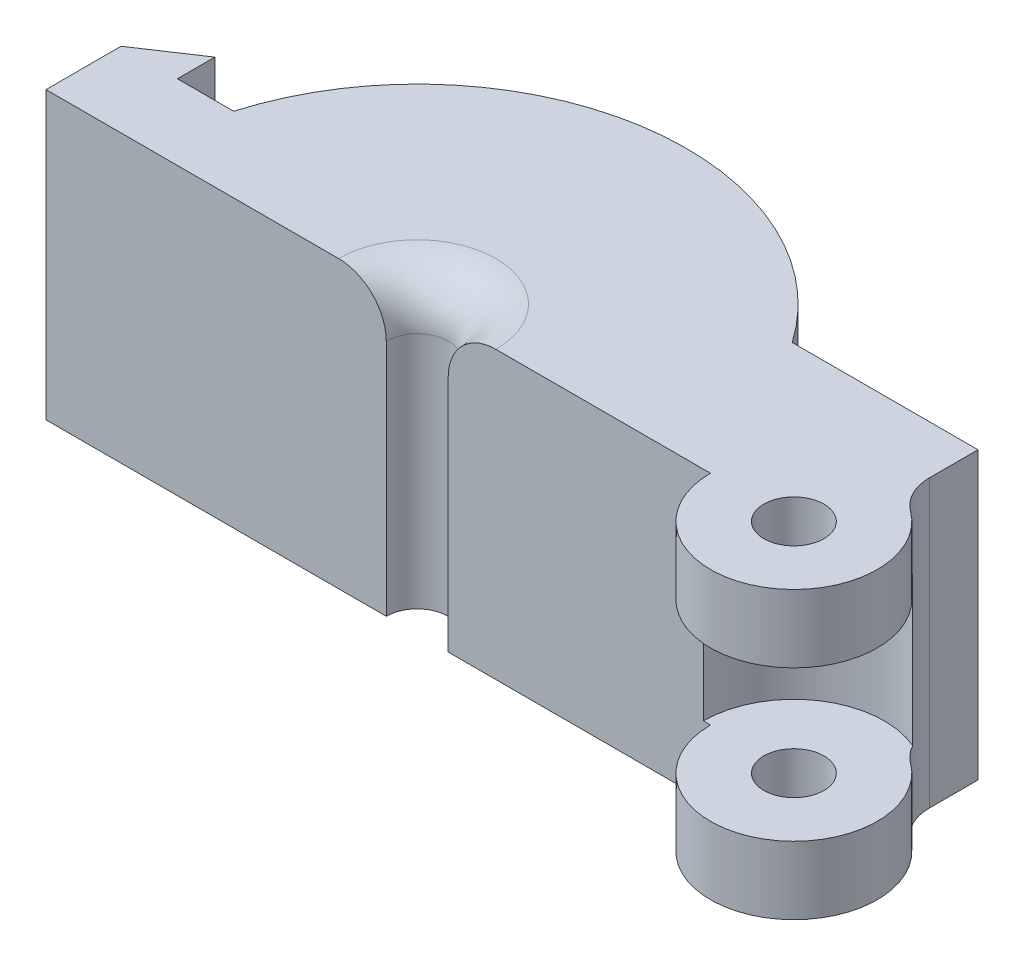
SolidWorks part; units mm, degrees
ref_plane "Front Plane" through (0, 0, 0) normal (0, 0, 1) x (1, 0, 0)
ref_plane "Top Plane" through (0, 0, 0) normal (0, 1, 0) x (1, 0, 0)
ref_plane "Right Plane" through (0, 0, 0) normal (1, 0, 0) x (0, 0, -1)
sketch "Sketch1" plane through (0, 0, 0) normal (0, 1, 0) x (1, 0, 0)
  line L0 (-13.7823, 0) -> (-1.651, 0)
  line L2 (0, 0) -> (0, 14.351) construction
  line L7 (15.625, 0) -> (1.651, 0)
  line L8 (11.7699, 8.2111) -> (21.67, 8.2111)
  line L9 (21.67, 8.2111) -> (21.67, 4.1471)
  line L10 (20.07, 0) -> (21.67, 0) construction
  line L16 (-13.7823, 4) -> (-16.7823, 4)
  line L17 (-19.7823, 0) -> (-19.7823, 4)
  line L18 (-19.7823, 4) -> (-16.7823, 6)
  line L19 (-16.7823, 6) -> (-16.7823, 4)
  line L21 (-13.7823, 0) -> (-19.7823, 0)
  arc A0 (1.651, 0) -> (-1.651, 0) centre (0, 0) ccw
  arc A1 (11.7699, 8.2111) -> (0, 14.351) centre (0, 0) ccw
  arc A3 (15.625, 0) -> (21.67, 4.1471) centre (20.07, 0) ccw
  circle A4 centre (20.07, 0) radius 1.6
  arc A5 (11.7699, 8.2111) -> (-13.7823, 4) centre (0, 0) ccw
  dimension "D1" = 3.302
  dimension "D2" = 12.7
  dimension "D5" = 4.445
  dimension "D6" = 3
  dimension "4.1mm" = 3.2
  dimension "D7" = 4
  dimension "D3" = 20.07
  dimension "D4" = 4.064
  dimension "D8" = 2
  dimension "D9" = 3
extrude "Boss-Extrude1" add sketch "Sketch1" along normal blind 15.24 contours A1 A5 L16 L19 L18 L17 L21 L0 A0 L7 A3 L9 L8 A4
ref_plane "Plane1" through (0, 7.62, 0) normal (0, 1, 0) x (1, 0, 0)
sketch "Sketch2" plane through (0, 7.62, 0) normal (0, 1, 0) x (1, 0, 0)
  circle A0 centre (20.07, 0) radius 4.826
  dimension "D1" = 9.652
extrude "Cut-Extrude1" cut sketch "Sketch2" against normal mid plane 8.001
fillet "Fillet1" [suppressed] radius 2.54
fillet "Fillet2" radius 2.54 1 edges at (0, 15.24, -1.651)
fillet "Fillet3" radius 2.54 1 edges at (21.67, 1.8097, -4.1471)
